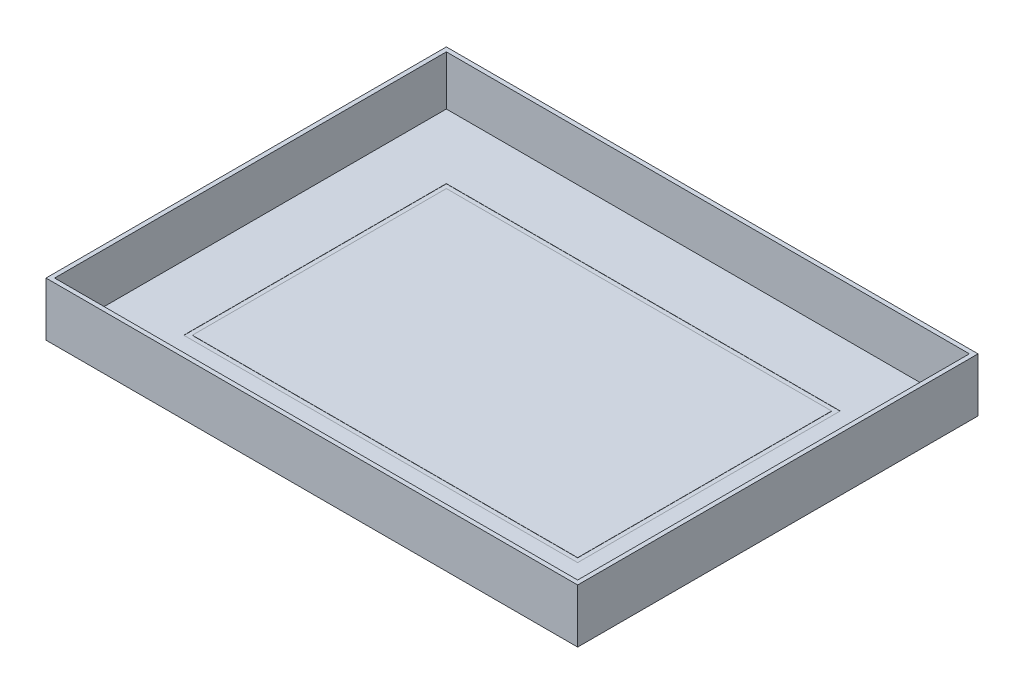
SolidWorks part; units mm, degrees
ref_plane "Спереди" through (0, 0, 0) normal (0, 0, 1) x (1, 0, 0)
ref_plane "Сверху" through (0, 0, 0) normal (0, 1, 0) x (1, 0, 0)
ref_plane "Справа" through (0, 0, 0) normal (1, 0, 0) x (0, 0, -1)
ref_plane "Плоскость4"
sketch "Эскиз1" plane through (0, 0, 0) normal (0, 1, 0) x (-1, 0, 0)
  line L0 (-1235, -930) -> (1235, -930)
  line L1 (1235, -930) -> (1235, 930)
  line L2 (1235, 930) -> (-1235, 930)
  line L3 (-1235, 930) -> (-1235, -930)
  line L4 (-1215, 910) -> (1215, 910)
  line L5 (1215, 910) -> (1215, -910)
  line L6 (1215, -910) -> (-1215, -910)
  line L7 (-1215, -910) -> (-1215, 910)
  dimension "D1" = 1820
  dimension "D2" = 2430
extrude "Выдавливание1" add sketch "Эскиз1" along normal blind 230 contours L2 L3 L0 L1 L6 L7 L4 L5
ref_plane "Плоскость5"
sketch "Эскиз2" plane through (0, 0, 0) normal (0, 1, 0) x (-1, 0, 0)
  line L0 (-1235, -930) -> (1235, -930)
  line L1 (1235, -930) -> (1235, 930)
  line L2 (1235, 930) -> (-1235, 930)
  line L3 (-1235, 930) -> (-1235, -930)
extrude "Выдавливание2" add sketch "Эскиз2" against normal blind 20
sketch "Эскиз3" plane through (0, 0, 0) normal (0, 1, 0) x (-1, 0, 0)
  line L0 (-915, 610) -> (-915, 0.0001)
  line L1 (-914.9999, 0) -> (-895.0001, 0)
  line L2 (-895, 0.0001) -> (-895, 590)
  line L3 (-895, 590) -> (895, 590)
  line L4 (895, 590) -> (895, 0.0001)
  line L5 (895.0001, 0) -> (914.9999, 0)
  line L6 (915, 0.0001) -> (915, 610)
  line L7 (915, 610) -> (-915, 610)
  line L8 (-895, -590) -> (-895, -0.0001)
  line L9 (-895, 0) -> (-915, 0)
  line L10 (-915, -0.0001) -> (-915, -610)
  line L11 (-915, -610) -> (915, -610)
  line L12 (915, -610) -> (915, -0.0001)
  line L13 (915, 0) -> (895, 0)
  line L14 (895, -0.0001) -> (895, -590)
  line L15 (895, -590) -> (-895, -590)
  line L16 (895, -330) -> (845, -330)
  line L17 (845, -330) -> (845, -350)
  line L18 (845, -350) -> (895, -350)
  line L19 (895, -350) -> (895, -330)
  line L20 (845, 330) -> (895, 330)
  line L21 (895, 330) -> (895, 350)
  line L22 (895, 350) -> (845, 350)
  line L23 (845, 350) -> (845, 330)
  circle A0 centre (465, -300) radius 25
  circle A1 centre (465, 300) radius 25
  arc A2 (914.9999, 0) -> (915, 0.0001) centre (914.9999, 0.0001) ccw
  arc A3 (895, 0.0001) -> (895.0001, 0) centre (895.0001, 0.0001) ccw
  arc A4 (-895.0001, 0) -> (-895, 0.0001) centre (-895.0001, 0.0001) ccw
  arc A5 (-915, 0.0001) -> (-914.9999, 0) centre (-914.9999, 0.0001) ccw
  arc A6 (895.0001, 0) -> (895, -0.0001) centre (895.0001, -0.0001) ccw
  arc A7 (915, -0.0001) -> (914.9999, 0) centre (914.9999, -0.0001) ccw
  arc A8 (-914.9999, 0) -> (-915, -0.0001) centre (-914.9999, -0.0001) ccw
  arc A9 (-895, -0.0001) -> (-895.0001, 0) centre (-895.0001, -0.0001) ccw
  dimension "D1" = 50
  dimension "D6" = 0.0001
  dimension "D7" = 0.0001
  dimension "D8" = 0.0001
  dimension "D9" = 0.0001
  dimension "D10" = 0.0001
  dimension "D11" = 0.0001
  dimension "D12" = 0.0001
  dimension "D13" = 0.0001
  dimension "D2" = 260
  dimension "D3" = 1810
  dimension "D4" = 50
  dimension "D5" = 20
extrude "Выдавливание3" cut sketch "Эскиз3" against normal blind 1 contours L8 A9 L1 A8 L10 L11 L12 A7 L5 A6 L14 L15 | L0 A5 L1 A4 L2 L3 L4 A3 L5 A2 L6 L7
